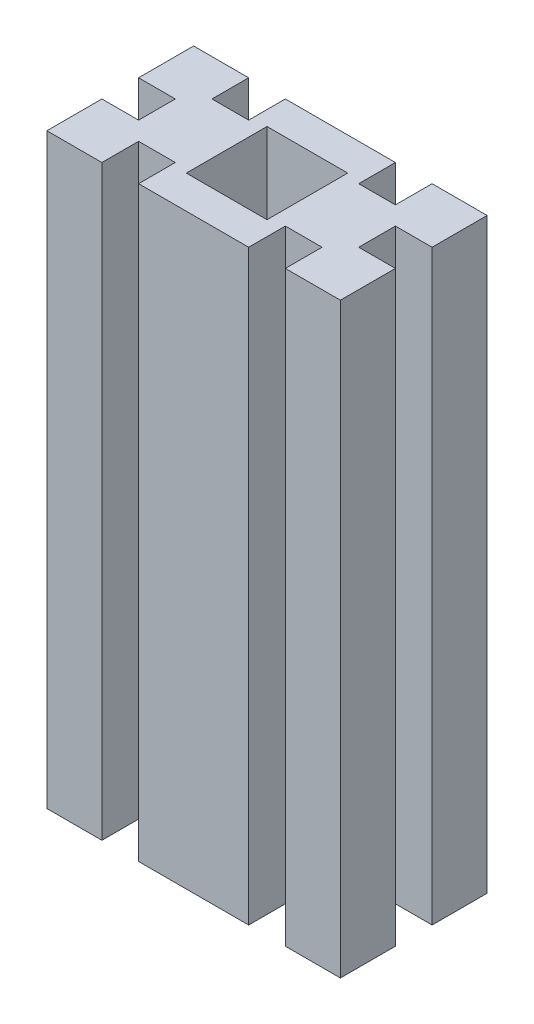
SolidWorks part; units mm, degrees
ref_plane "Front Plane" through (0, 0, 0) normal (0, 0, 1) x (1, 0, 0)
ref_plane "Top Plane" through (0, 0, 0) normal (0, 1, 0) x (1, 0, 0)
ref_plane "Right Plane" through (0, 0, 0) normal (1, 0, 0) x (0, 0, -1)
sketch "Sketch1" plane through (0, 0, 0) normal (0, 1, 0) x (1, 0, 0)
  line L1 (20, -10) -> (-20, -10)
  line L2 (20, -10) -> (20, 10)
  line L3 (20, 10) -> (-20, 10)
  line L4 (-20, -10) -> (-20, 10)
  line L5 (20, -10) -> (-20, 10) construction
  line L6 (20, 10) -> (-20, -10) construction
  point P0 (0, 0)
  dimension "D1" = 20
  dimension "D2" = 40
extrude "Body" add sketch "Sketch1" along normal blind 80
sketch "Sketch2" plane through (0, 80, 0) normal (0, 1, 0) x (1, 0, 0)
  line L0 (20, 10) -> (-20, 10) construction
  line L1 (-12.5, 10) -> (-7.5, 10)
  line L2 (-12.5, 10) -> (-12.5, 5)
  line L3 (-12.5, 5) -> (-7.5, 5)
  line L4 (-7.5, 10) -> (-7.5, 5)
  line L5 (-20, 10) -> (-20, -10) construction
  line L6 (-20, 2.5) -> (-15, 2.5)
  line L7 (-20, 2.5) -> (-20, -2.5)
  line L8 (-20, -2.5) -> (-15, -2.5)
  line L9 (-15, 2.5) -> (-15, -2.5)
  line L10 (-20, -10) -> (20, -10) construction
  line L11 (-12.5, -10) -> (-7.5, -10)
  line L12 (-12.5, -10) -> (-12.5, -5)
  line L13 (-12.5, -5) -> (-7.5, -5)
  line L14 (-7.5, -10) -> (-7.5, -5)
  line L15 (0, -1000) -> (0, 49000) construction
  line L16 (7.5, -10) -> (7.5, -5)
  line L17 (12.5, -5) -> (7.5, -5)
  line L18 (12.5, -10) -> (12.5, -5)
  line L19 (12.5, -10) -> (7.5, -10)
  line L20 (15, 2.5) -> (15, -2.5)
  line L21 (20, -2.5) -> (15, -2.5)
  line L22 (20, 2.5) -> (20, -2.5)
  line L23 (20, 2.5) -> (15, 2.5)
  line L24 (7.5, 10) -> (7.5, 5)
  line L25 (12.5, 5) -> (7.5, 5)
  line L26 (12.5, 10) -> (12.5, 5)
  line L27 (12.5, 10) -> (7.5, 10)
  line L29 (5.5, 5.5) -> (-5.5, 5.5)
  line L30 (5.5, 5.5) -> (5.5, -5.5)
  line L31 (5.5, -5.5) -> (-5.5, -5.5)
  line L32 (-5.5, 5.5) -> (-5.5, -5.5)
  line L33 (5.5, 5.5) -> (-5.5, -5.5) construction
  line L34 (5.5, -5.5) -> (-5.5, 5.5) construction
  point P18 (-15, 0)
  point P35 (0, 0)
  dimension "D1" = 5
  dimension "D2" = 5
  dimension "D3" = 7.5
  dimension "D4" = 11
extrude "Profilage" cut sketch "Sketch2" against normal through all
